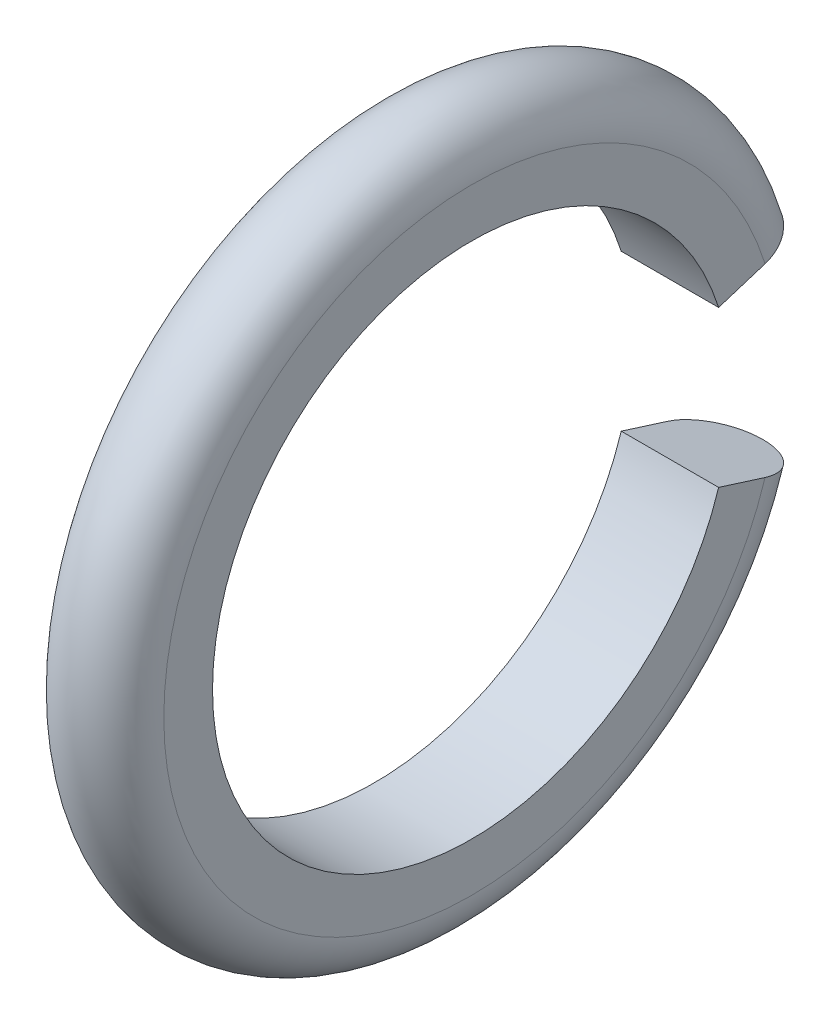
SolidWorks part; units mm, degrees
ref_plane "Front Plane" through (0, 0, 0) normal (0, 0, 1) x (1, 0, 0)
ref_plane "Top Plane" through (0, 0, 0) normal (0, 1, 0) x (1, 0, 0)
ref_plane "Right Plane" through (0, 0, 0) normal (1, 0, 0) x (0, 0, -1)
sketch "Sketch1" plane through (0, 0, 0) normal (0, 0, 1) x (1, 0, 0)
  line L0 (0, -55) -> (0, 55) construction
  line L1 (1.5875, 10.033) -> (1.5875, 8.4455)
  line L2 (1.5875, 8.4455) -> (-1.5875, 8.4455)
  line L3 (-1.5875, 8.4455) -> (-1.5875, 10.033)
  line L4 (55, 0) -> (-55, 0) construction
  line L5 (-5.0091, 0) -> (5.5531, 0) construction
  arc A0 (1.5875, 10.033) -> (-1.5875, 10.033) centre (0, 10.033) ccw
  dimension "D1" = 1.5875
  dimension "D2" = 1.5875
  dimension "D3" = 10.033
revolve "Revolve1" add sketch "Sketch1" angle 360 about L5
sketch "Sketch2" plane through (0, 0, 0) normal (1, 0, 0) x (0, 0, -1)
  line L0 (0, 0) -> (15.1953, 4.7911)
  line L1 (15.1953, 4.7911) -> (15.202, -4.7932)
  line L2 (15.202, -4.7932) -> (0, 0)
  line L3 (1.7463, 0) -> (-1.7463, 0) construction
  dimension "D1" = 35
  dimension "D2" = 17.5
extrude "Cut-Extrude1" cut sketch "Sketch2" against normal through all both and the other way through all
